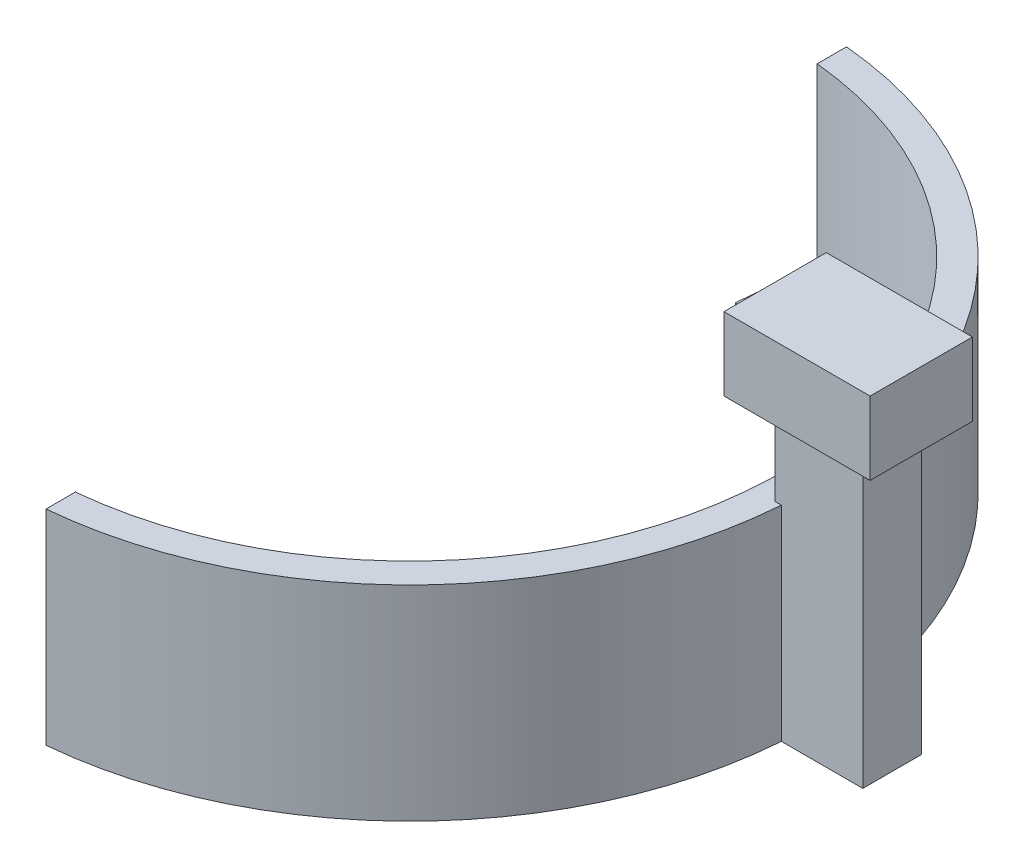
SolidWorks part; units mm, degrees
ref_plane "Front Plane" through (0, 0, 0) normal (0, 0, 1) x (1, 0, 0)
ref_plane "Top Plane" through (0, 0, 0) normal (0, 1, 0) x (1, 0, 0)
ref_plane "Right Plane" through (0, 0, 0) normal (1, 0, 0) x (0, 0, -1)
sketch "Sketch1" plane through (0, 0, 0) normal (0, 1, 0) x (1, 0, 0)
  line L4 (2.5, 27.3861) -> (2.5, 25.3772)
  line L6 (-2.5, 0) -> (2.5, 0) construction
  line L7 (2.5, -25.3772) -> (2.5, -27.3861)
  arc A2 (2.5, -27.3861) -> (2.5, 27.3861) centre (0, 0) ccw
  arc A5 (2.5, -25.3772) -> (2.5, 25.3772) centre (0, 0) ccw
  point P4 (24.3858, 7.4555)
  point P12 (26.2984, 8.0402)
extrude "Boss-Extrude1" add sketch "Sketch1" along normal blind 12
sketch "Sketch2" plane through (0, 0, 0) normal (0, 1, 0) x (1, 0, 0)
  line L0 (2.5, 27.3861) -> (1.8636, 20.4151)
  line L1 (2.5, -27.3861) -> (1.8636, -20.4151)
  arc A0 (2.5, 27.3861) -> (2.5, -27.3861) centre (0, 0) cw
  arc A1 (1.8636, 20.4151) -> (1.8636, -20.4151) centre (0, 0) cw
  dimension "D1" = 7
extrude "Boss-Extrude2" add sketch "Sketch2" against normal blind 2
sketch "Sketch4" plane through (0, -2, 0) normal (0, 1, 0) x (1, 0, 0)
  line L1 (27, 2) -> (33, 2)
  line L2 (27, 2) -> (27, -2)
  line L3 (27, -2) -> (33, -2)
  line L4 (33, 2) -> (33, -2)
  line L5 (30, -2) -> (30, 2) construction
  line L6 (27, 0) -> (33, 0) construction
  point P0 (30, 0)
  dimension "D1" = 6
  dimension "D2" = 4
  dimension "D3" = 30
extrude "Boss-Extrude3" add sketch "Sketch4" along normal blind 20
sketch "Sketch5" plane through (0, 18, 0) normal (0, 1, 0) x (1, 0, 0)
  line L0 (33, 2) -> (27, 2) construction
  line L1 (25, 3.5) -> (35, 3.5)
  line L2 (25, 3.5) -> (25, -3.5)
  line L3 (25, -3.5) -> (35, -3.5)
  line L4 (35, 3.5) -> (35, -3.5)
  line L5 (25, 3.5) -> (35, -3.5) construction
  line L6 (25, -3.5) -> (35, 3.5) construction
  line L7 (33, -2) -> (33, 2) construction
  point P0 (30, 0)
  dimension "D1" = 2
  dimension "D2" = 3
  dimension "D3" = 10
  dimension "D4" = 7
extrude "Boss-Extrude4" add sketch "Sketch5" along normal blind 5
